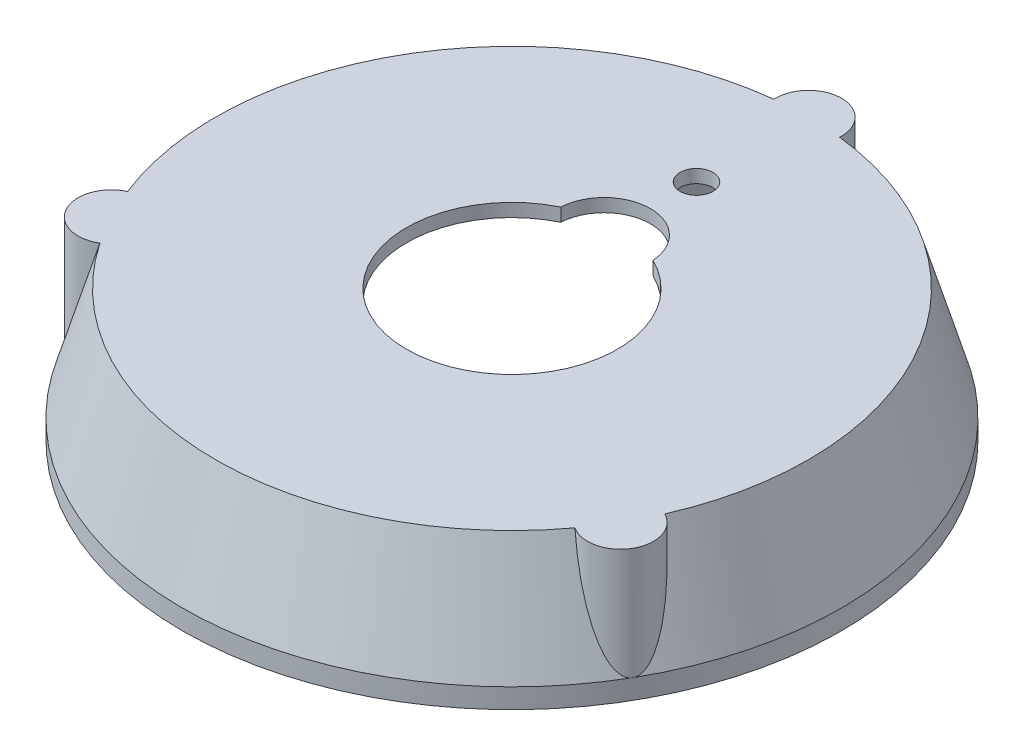
SolidWorks part; units mm, degrees
ref_plane "Ebene vorne" through (0, 0, 0) normal (0, 0, 1) x (1, 0, 0)
ref_plane "Ebene oben" through (0, 0, 0) normal (0, 1, 0) x (1, 0, 0)
ref_plane "Ebene rechts" through (0, 0, 0) normal (1, 0, 0) x (0, 0, -1)
sketch "Skizze1" plane through (0, 0, 0) normal (0, 1, 0) x (1, 0, 0)
  line L0 (0, 0) -> (0, 45) construction
  line L1 (0, 0) -> (38.9711, -22.5) construction
  line L2 (0, 0) -> (-39.8015, -20.9962) construction
  circle A0 centre (0, 0) radius 50
  circle A1 centre (0, 0) radius 45 construction
  arc A5 (-4.9923, 44.7222) -> (4.9923, 44.7222) centre (0, 45) ccw
  arc A6 (-41.8851, -16.451) -> (-37.2265, -25.2821) centre (-39.8015, -20.9962) cw
  arc A7 (41.2267, -18.0377) -> (36.2344, -26.6846) centre (38.9711, -22.5) ccw
  arc A8 (-4.9923, 44.7222) -> (-41.8851, -16.451) centre (0, 0) ccw
  arc A9 (4.9923, 44.7222) -> (41.2267, -18.0377) centre (0, 0) cw
  arc A10 (36.2344, -26.6846) -> (-37.2265, -25.2821) centre (0, 0) cw
extrude "Aufsatz-Linear austragen1" add sketch "Skizze1" along normal blind 3
sketch "Skizze4" plane through (0, 0, 0) normal (0, 0, 1) x (1, 0, 0)
  line L0 (-50, 3) -> (-45, 3) construction
  line L1 (50, 3) -> (-50, 3) construction
  line L2 (-45, 3) -> (-45, 20) construction
  line L3 (-45, 20) -> (-50, 3)
  line L4 (-45, 3) -> (-40, 20)
  line L5 (-40, 20) -> (-45, 20)
  line L6 (-50, 3) -> (-45, 3)
  line L7 (0, 0) -> (0, 70) construction
revolve "Rotation1" add sketch "Skizze4" angle 360 about L7
sketch "Skizze7" plane through (0, 0, 0) normal (0, -1, 0) x (1, 0, 0)
  circle A0 centre (-39.8015, 20.9962) radius 5.0306
  circle A1 centre (0, -45) radius 5
  circle A2 centre (38.9711, 22.5) radius 5
extrude "Aufsatz-Linear austragen4" add sketch "Skizze7" against normal blind 20
sketch "Skizze8" plane through (0, 20, 0) normal (0, 1, 0) x (1, 0, 0)
  circle A0 centre (0, 0) radius 45
extrude "Aufsatz-Linear austragen5" add sketch "Skizze8" against normal blind 2
sketch "Skizze9" plane through (0, 20, 0) normal (0, 1, 0) x (1, 0, 0)
  line L0 (0, 0) -> (0, 14) construction
  line L1 (0, 14) -> (0, 28) construction
  circle A0 centre (0, 0) radius 16 construction
  arc A1 (-1.8858, 20.7412) -> (6.989, 14.3929) centre (0, 14) cw
  arc A2 (-1.8858, 20.7412) -> (-6.989, 14.3929) centre (0, 14) ccw
  arc A3 (-6.989, 14.3929) -> (6.989, 14.3929) centre (0, 0) ccw
  circle A4 centre (0, 28) radius 2.5
extrude "Schnitt-Linear austragen1" cut sketch "Skizze9" against normal blind 2 contours A2 A3 A1 | A4
sketch "Skizze10" plane through (0, 0, 0) normal (0, -1, 0) x (1, 0, 0)
  circle A0 centre (-39.8015, 20.9962) radius 1.9
  circle A1 centre (38.9711, 22.5) radius 1.9
  circle A2 centre (0, -45) radius 1.9
extrude "Schnitt-Linear austragen2" cut sketch "Skizze10" against normal blind 18
